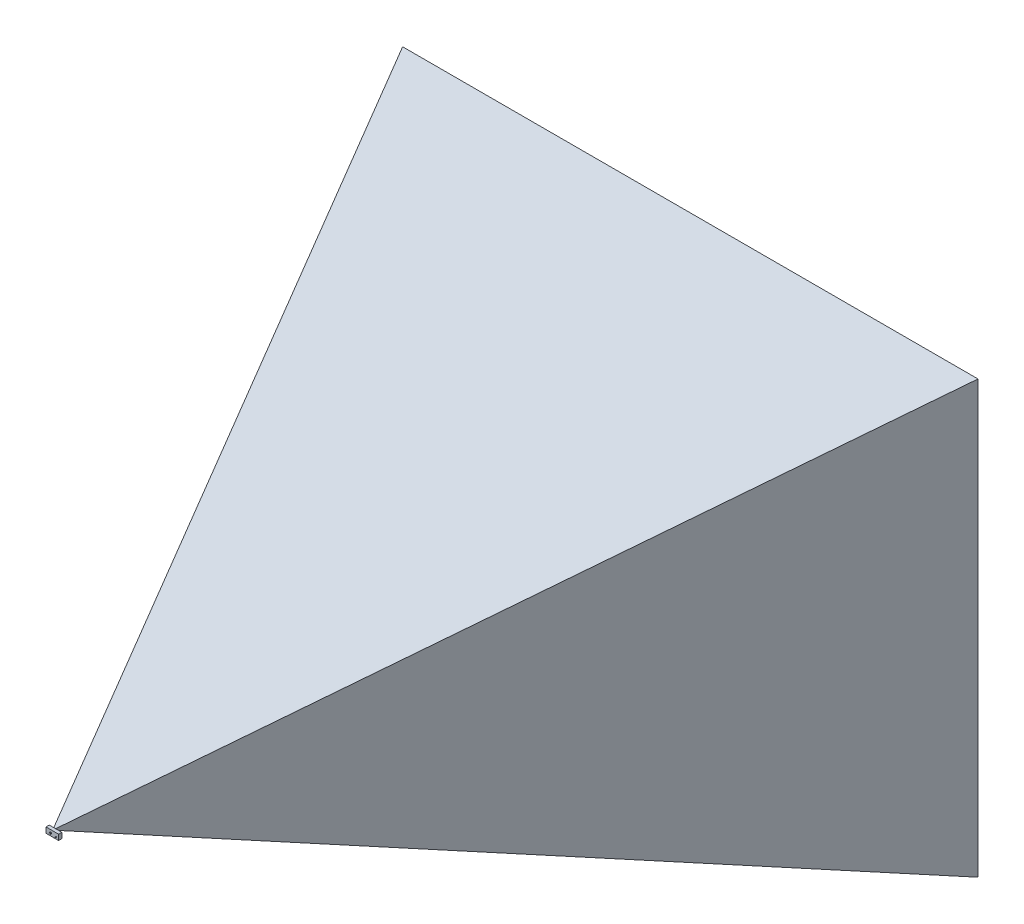
SolidWorks part; units mm, degrees
material "6061-T6 (SS)"
ref_plane "Front Plane" through (0, 0, 0) normal (0, 0, 1) x (1, 0, 0)
ref_plane "Top Plane" through (0, 0, 0) normal (0, 1, 0) x (1, 0, 0)
ref_plane "Right Plane" through (0, 0, 0) normal (1, 0, 0) x (0, 0, -1)
sketch "Sketch1" plane through (0, 0, 0) normal (0, 0, 1) x (1, 0, 0)
  line L0 (0, 15.5575) -> (70.993, 15.5575) construction
  line L1 (0, 0) -> (70.993, 0)
  line L2 (0, 0) -> (0, 31.115)
  line L3 (0, 31.115) -> (70.993, 31.115)
  line L4 (70.993, 0) -> (70.993, 31.115)
  dimension "D1" = 70.993
  dimension "D2" = 31.115
extrude "Boss-Extrude1" add sketch "Sketch1" along normal blind 18.415 contours L3 L4 L1 L2
sketch "Sketch2" plane through (0, 0, 18.415) normal (0, 0, 1) x (1, 0, 0)
  line L0 (15.875, 25.7175) -> (55.118, 25.7175) construction
  line L1 (5.715, 15.5575) -> (27.94, 15.5575) construction
  line L2 (55.118, 5.3975) -> (15.875, 5.3975) construction
  line L3 (27.94, 15.5575) -> (53.848, 15.5575) construction
  line L4 (5.715, 15.5575) -> (0, 15.5575) construction
  line L5 (0, 0) -> (0, 31.115) construction
  line L6 (35.4965, 25.7175) -> (35.4965, 31.115) construction
  line L7 (0, 31.115) -> (70.993, 31.115) construction
  line L8 (65.278, 15.5575) -> (70.993, 15.5575) construction
  line L9 (70.993, 0) -> (70.993, 31.115) construction
  line L10 (35.4965, 5.3975) -> (35.4965, 0) construction
  line L11 (0, 0) -> (70.993, 0) construction
  line L12 (24.13, 12.3825) -> (31.75, 12.3825)
  line L13 (24.13, 12.3825) -> (24.13, 18.7325)
  line L14 (24.13, 18.7325) -> (31.75, 18.7325)
  line L15 (31.75, 12.3825) -> (31.75, 18.7325)
  line L16 (24.13, 12.3825) -> (31.75, 18.7325) construction
  line L17 (24.13, 18.7325) -> (31.75, 12.3825) construction
  line L18 (53.848, 15.5575) -> (60.198, 15.5575) construction
  line L19 (60.198, 15.5575) -> (60.198, 20.32) construction
  line L21 (53.848, 20.32) -> (53.848, 15.5575) construction
  line L22 (53.848, 15.5575) -> (53.848, 10.795) construction
  line L24 (60.198, 10.795) -> (60.198, 15.5575) construction
  line L25 (60.198, 15.5575) -> (65.278, 15.5575) construction
  arc A0 (15.875, 25.7175) -> (15.875, 5.3975) centre (15.875, 15.5575) ccw construction
  arc A1 (55.118, 5.3975) -> (55.118, 25.7175) centre (55.118, 15.5575) ccw construction
  arc A2 (60.198, 20.32) -> (53.848, 20.32) centre (57.023, 20.32) ccw construction
  arc A3 (53.848, 10.795) -> (60.198, 10.795) centre (57.023, 10.795) ccw construction
  circle A4 centre (57.023, 10.795) radius 1.905
  point P37 (57.023, 23.495)
  point P38 (57.023, 7.62)
  dimension "D1" = 5.715
  dimension "D3" = 24.13
  dimension "D6" = 15.875
  dimension "D9" = 13.97
  dimension "D2" = 3.81
  dimension "D4" = 7.62
  dimension "D5" = 6.35
  dimension "D7" = 5.08
  dimension "D8" = 20.32
extrude "Boss-Extrude2" add sketch "Sketch2" along normal blind 6.35
sketch "Sketch3" plane through (0, 0, 0) normal (0, 0, -1) x (-1, 0, 0)
  line L0 (-19.05, 15.5575) -> (0, 15.5575) construction
  line L3 (0, 0) -> (0, 31.115) construction
  circle A0 centre (-19.05, 15.5575) radius 5.715
  dimension "D1" = 11.43
  dimension "D2" = 19.05
extrude "Cut-Extrude1" cut sketch "Sketch3" against normal blind 2.54 contours A0
ref_plane "Plane1" through (0, 0, -3603.244) normal (0, 0, -1) x (-1, 0, 0)
sketch "Sketch4" plane through (0, 0, -3603.244) normal (0, 0, -1) x (-1, 0, 0)
  line L1 (-1644.65, 1234.7575) -> (1606.55, 1234.7575)
  line L2 (-1644.65, 1234.7575) -> (-1644.65, -1203.6425)
  line L3 (-1644.65, -1203.6425) -> (1606.55, -1203.6425)
  line L4 (1606.55, 1234.7575) -> (1606.55, -1203.6425)
  line L5 (-1644.65, 1234.7575) -> (1606.55, -1203.6425) construction
  line L6 (-1644.65, -1203.6425) -> (1606.55, 1234.7575) construction
  point P0 (-19.05, 15.5575)
  dimension "D1" = 3251.2
  dimension "D2" = 2438.4
sketch "Sketch5" plane through (0, 0, 0) normal (0, 0, -1) x (-1, 0, 0)
  circle A0 centre (-19.05, 15.5575) radius 5.715 construction
  point P0 (-19.05, 15.5575)
  point P1 (0, 0)
surface "Surface-Loft1"
